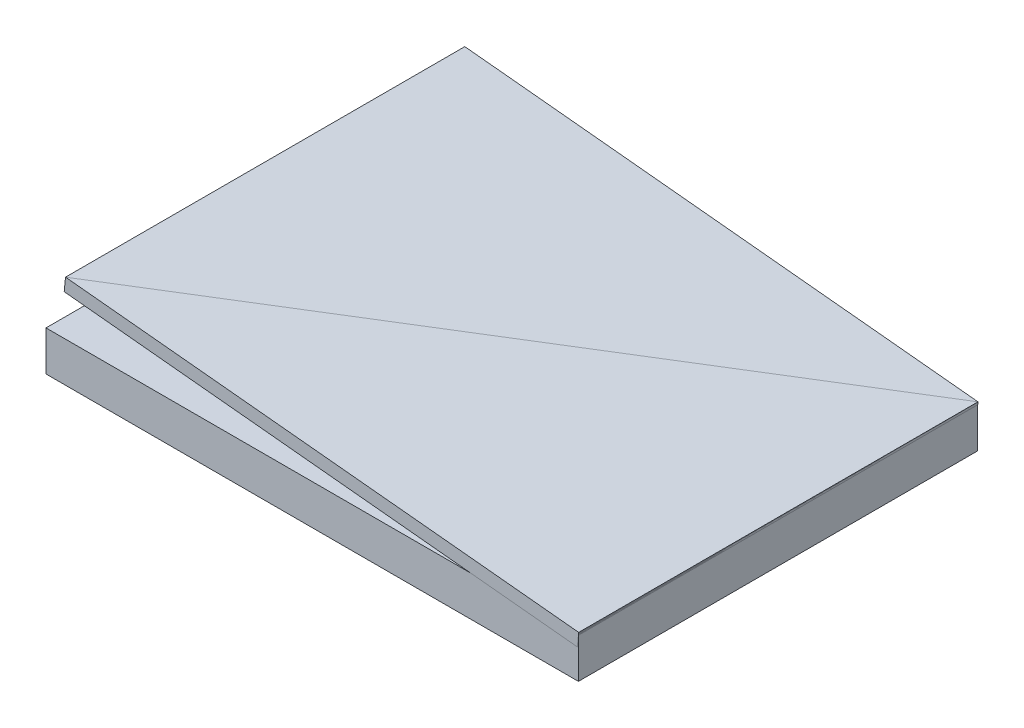
SolidWorks part; units mm, degrees
other "COLL.BOX-Boss-Extrude2"
other "Estrusione5"
ref_plane "Piano frontale" through (0, 0, 0) normal (0, 0, 1) x (1, 0, 0)
ref_plane "Piano superiore" through (0, 0, 0) normal (0, 1, 0) x (1, 0, 0)
ref_plane "Piano destro" through (0, 0, 0) normal (1, 0, 0) x (0, 0, -1)
sketch "Sketch1" plane through (0, 0, 0) normal (0, 0, 1) x (1, 0, 0)
  line L1 (-128.788, 533.9944) -> (271.212, 533.9944)
  line L2 (-128.788, 533.9944) -> (-128.788, 503.9944)
  line L3 (-128.788, 503.9944) -> (271.212, 503.9944)
  line L4 (271.212, 533.9944) -> (271.212, 503.9944)
  dimension "D1" = 30
  dimension "D2" = 400
extrude "Boss-Extrude1" add sketch "Sketch1" along normal mid plane 300
sketch "Sketch2" plane through (0, 533.9944, 0) normal (0, 1, 0) x (1, 0, 0)
  line L0 (-128.788, 0) -> (271.212, 0)
  line L1 (-128.788, 150) -> (-128.788, -150) construction
  line L2 (271.212, 150) -> (271.212, -150) construction
  line L3 (71.212, 0) -> (71.212, -150)
  line L4 (271.212, -150) -> (-128.788, -150) construction
  line L5 (71.212, 0) -> (71.212, 150)
  line L6 (271.212, 150) -> (-128.788, 150) construction
sketch "Schizzo9" plane through (0, 0, 0) normal (0, 0, 1) x (1, 0, 0)
  line L0 (271.212, 533.9944) -> (-114.3344, 572.3414)
  line L1 (271.212, 533.9944) -> (271.4099, 535.9846)
  line L2 (-114.3344, 572.3414) -> (-114.1365, 574.3316)
  line L3 (271.4099, 535.9846) -> (-114.1365, 574.3316)
  dimension "D1" = 2
  dimension "D2" = 385.5464
extrude "Estrusione-Estrusione5" add sketch "Schizzo9" along normal up to vertex (150 mm away) and the other way up to vertex (150 mm away) separate body up to point (-128.788, 533.9945, 150) other way up to point (-128.788, 533.9945, -150)
move or copy body "Body-copy_collisionbox_for_visualize" [suppressed] bodies to move or copy 106 copy yes number of copies 1 translate (0, 0, 0)
sketch "Sketch3" plane through (55.4461, 557.4647, 0) normal (0.099, 0.9951, 0) x (0.9951, -0.099, 0)
  line L4 (217.0294, -150) -> (217.0294, 150)
  line L5 (217.0294, 150) -> (-170.4193, 150)
  line L6 (-170.4193, 150) -> (-170.4193, -150)
  line L7 (-170.4193, -150) -> (217.0294, -150)
  line L8 (217.0294, -150) -> (217.0294, 150)
  line L9 (217.0294, 150) -> (-170.4193, 150)
  line L10 (-170.4193, 150) -> (-170.4193, -150)
  line L11 (-170.4193, -150) -> (217.0294, -150)
  dimension "D1" = 0
extrude "Boss-Extrude2" add sketch "Sketch3" against normal blind 10 separate body
